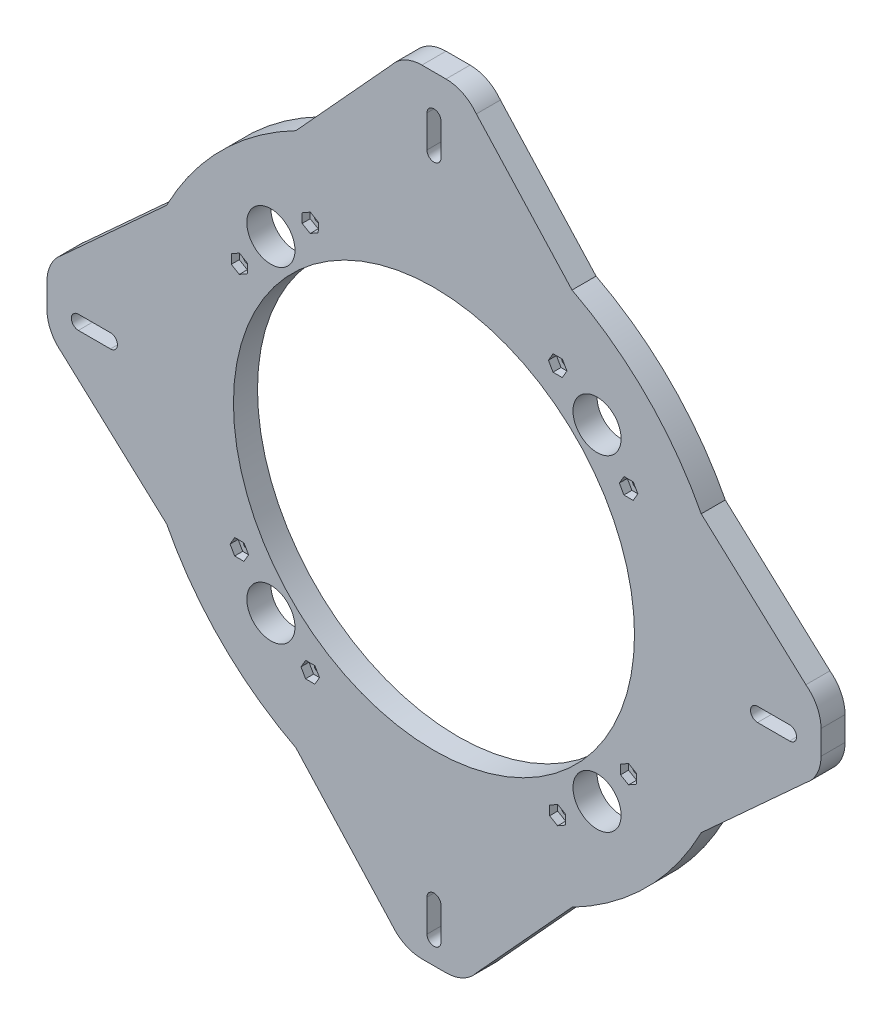
SolidWorks part; units mm, degrees
ref_plane "Plan de face" through (0, 0, 0) normal (0, 0, 1) x (1, 0, 0)
ref_plane "Plan de dessus" through (0, 0, 0) normal (0, 1, 0) x (1, 0, 0)
ref_plane "Plan de droite" through (0, 0, 0) normal (1, 0, 0) x (0, 0, -1)
sketch "Esquisse1" plane through (0, 0, 0) normal (0, 0, 1) x (1, 0, 0)
  circle A1 centre (0, 0) radius 150
  circle A13 centre (0, 0) radius 100
  dimension "D1" = 300
  dimension "D2" = 200
extrude "Boss.-Extru.1" add sketch "Esquisse1" along normal blind 12
sketch "Esquisse2" plane through (0, 0, 12) normal (0, 0, 1) x (1, 0, 0)
  line L0 (0, 100) -> (0, 150) construction
  circle A1 centre (0, 0) radius 150 construction
  circle A2 centre (0, 125) radius 17.5
  circle A3 centre (73.4732, 101.1271) radius 17.5
  circle A4 centre (118.8821, 38.6271) radius 17.5
  circle A5 centre (118.8821, -38.6271) radius 17.5
  circle A6 centre (73.4732, -101.1271) radius 17.5
  circle A7 centre (0, -125) radius 17.5
  circle A8 centre (-73.4732, -101.1271) radius 17.5
  circle A9 centre (-118.8821, -38.6271) radius 17.5
  circle A10 centre (-118.8821, 38.6271) radius 17.5
  circle A11 centre (-73.4732, 101.1271) radius 17.5
  point P29 (0, 0)
  dimension "D1" = 35
  dimension "D2" = 10
extrude "Boss.-Extru.2" add sketch "Esquisse2" along normal blind 12
sketch "Esquisse3" plane through (0, 0, 24) normal (0, 0, 1) x (1, 0, 0)
  circle A0 centre (0, 125) radius 10.5
  circle A1 centre (73.4732, 101.1271) radius 10.5
  circle A2 centre (118.8821, 38.6271) radius 10.5
  circle A3 centre (118.8821, -38.6271) radius 10.5
  circle A4 centre (73.4732, -101.1271) radius 10.5
  circle A5 centre (0, -125) radius 10.5
  circle A6 centre (-73.4732, -101.1271) radius 10.5
  circle A7 centre (-118.8821, -38.6271) radius 10.5
  circle A8 centre (-118.8821, 38.6271) radius 10.5
  circle A9 centre (-73.4732, 101.1271) radius 10.5
  point P23 (0, 0)
  dimension "D1" = 21
  dimension "D2" = 10
extrude "Boss.-Extru.3" add sketch "Esquisse3" along normal blind 9
sketch "Esquisse4" plane through (0, 0, 12) normal (0, 0, 1) x (1, 0, 0)
  line L0 (0, 0) -> (0, 182.4914) construction
  line L1 (-14, 145) -> (-14, 185)
  line L2 (-6, 193) -> (6, 193)
  line L3 (14, 185) -> (14, 145)
  line L4 (-14, 145) -> (14, 145)
  line L5 (0, 154.5361) -> (0, 184.5361) construction
  line L6 (-3.75, 154.5361) -> (-3.75, 184.5361)
  line L7 (3.75, 154.5361) -> (3.75, 184.5361)
  line L8 (145, 14) -> (145, -14)
  line L9 (185, -14) -> (145, -14)
  line L10 (193, 6) -> (193, -6)
  line L11 (145, 14) -> (185, 14)
  line L12 (154.5361, -3.75) -> (184.5361, -3.75)
  line L13 (154.5361, 3.75) -> (184.5361, 3.75)
  line L14 (154.5361, 0) -> (184.5361, 0) construction
  line L15 (14, -145) -> (-14, -145)
  line L16 (-14, -185) -> (-14, -145)
  line L17 (6, -193) -> (-6, -193)
  line L18 (14, -145) -> (14, -185)
  line L19 (-3.75, -154.5361) -> (-3.75, -184.5361)
  line L20 (3.75, -154.5361) -> (3.75, -184.5361)
  line L21 (0, -154.5361) -> (0, -184.5361) construction
  line L22 (-145, -14) -> (-145, 14)
  line L23 (-185, 14) -> (-145, 14)
  line L24 (-193, -6) -> (-193, 6)
  line L25 (-145, -14) -> (-185, -14)
  line L26 (-154.5361, 3.75) -> (-184.5361, 3.75)
  line L27 (-154.5361, -3.75) -> (-184.5361, -3.75)
  line L28 (-154.5361, 0) -> (-184.5361, 0) construction
  arc A0 (14, 185) -> (6, 193) centre (6, 185) ccw
  arc A1 (-6, 193) -> (-14, 185) centre (-6, 185) ccw
  arc A2 (-3.75, 154.5361) -> (3.75, 154.5361) centre (0, 154.5361) ccw
  arc A3 (3.75, 184.5361) -> (-3.75, 184.5361) centre (0, 184.5361) ccw
  arc A4 (185, -14) -> (193, -6) centre (185, -6) ccw
  arc A5 (193, 6) -> (185, 14) centre (185, 6) ccw
  arc A6 (154.5361, 3.75) -> (154.5361, -3.75) centre (154.5361, 0) ccw
  arc A7 (184.5361, -3.75) -> (184.5361, 3.75) centre (184.5361, 0) ccw
  arc A8 (-14, -185) -> (-6, -193) centre (-6, -185) ccw
  arc A9 (6, -193) -> (14, -185) centre (6, -185) ccw
  arc A10 (3.75, -154.5361) -> (-3.75, -154.5361) centre (0, -154.5361) ccw
  arc A11 (-3.75, -184.5361) -> (3.75, -184.5361) centre (0, -184.5361) ccw
  arc A12 (-185, 14) -> (-193, 6) centre (-185, 6) ccw
  arc A13 (-193, -6) -> (-185, -14) centre (-185, -6) ccw
  arc A14 (-154.5361, -3.75) -> (-154.5361, 3.75) centre (-154.5361, 0) ccw
  arc A15 (-184.5361, 3.75) -> (-184.5361, -3.75) centre (-184.5361, 0) ccw
  point P9 (14, 193)
  point P13 (0, 169.5361)
  point P31 (169.5361, 0)
  point P46 (0, -169.5361)
  point P61 (-169.5361, 0)
  point P67 (0, 0)
  dimension "D5" = 8
  dimension "D1" = 145
  dimension "D2" = 48
  dimension "D3" = 14
  dimension "D4" = 14
  dimension "D6" = 7.5
  dimension "D7" = 30
  dimension "D8" = 4
extrude "Boss.-Extru.4" add sketch "Esquisse4" against normal blind 12
sketch "Esquisse5" plane through (0, 0, 12) normal (0, 0, 1) x (1, 0, 0)
  line L0 (-6, 193) -> (6, 193)
  line L1 (0, 0) -> (0, 81.7403) construction
  line L2 (21.1389, 185.4745) -> (78.6763, 122.5066)
  line L3 (-21.1389, 185.4745) -> (-78.6763, 122.5066)
  line L4 (-78.6763, 122.5066) -> (0, 146.4026)
  line L5 (0, 146.4026) -> (78.6763, 122.5066)
  line L6 (146.4026, 0) -> (122.5066, -78.6763)
  line L7 (185.4745, -21.1389) -> (122.5066, -78.6763)
  line L8 (193, 6) -> (193, -6)
  line L9 (185.4745, 21.1389) -> (122.5066, 78.6763)
  line L10 (122.5066, 78.6763) -> (146.4026, 0)
  line L11 (0, -146.4026) -> (-78.6763, -122.5066)
  line L12 (-21.1389, -185.4745) -> (-78.6763, -122.5066)
  line L13 (6, -193) -> (-6, -193)
  line L14 (21.1389, -185.4745) -> (78.6763, -122.5066)
  line L15 (78.6763, -122.5066) -> (0, -146.4026)
  line L16 (-146.4026, 0) -> (-122.5066, 78.6763)
  line L17 (-185.4745, 21.1389) -> (-122.5066, 78.6763)
  line L18 (-193, -6) -> (-193, 6)
  line L19 (-185.4745, -21.1389) -> (-122.5066, -78.6763)
  line L20 (-122.5066, -78.6763) -> (-146.4026, 0)
  arc A0 (6, 193) -> (21.1389, 185.4745) centre (6, 174.0098) cw
  arc A1 (-6, 193) -> (-21.1389, 185.4745) centre (-6, 174.0098) ccw
  arc A2 (193, -6) -> (185.4745, -21.1389) centre (174.0098, -6) cw
  arc A3 (193, 6) -> (185.4745, 21.1389) centre (174.0098, 6) ccw
  arc A4 (-6, -193) -> (-21.1389, -185.4745) centre (-6, -174.0098) cw
  arc A5 (6, -193) -> (21.1389, -185.4745) centre (6, -174.0098) ccw
  arc A6 (-193, 6) -> (-185.4745, 21.1389) centre (-174.0098, 6) cw
  arc A7 (-193, -6) -> (-185.4745, -21.1389) centre (-174.0098, -6) ccw
  point P45 (0, 0)
  dimension "D1" = 4
extrude "Boss.-Extru.5" add sketch "Esquisse5" against normal blind 12
sketch "Esquisse6" plane through (0, 0, 12) normal (0, 0, 1) x (1, 0, 0)
  line L0 (0, 0) -> (0, 165.5959) construction
  line L1 (0, 157.5959) -> (0, 173.5959) construction
  line L2 (-3.5, 157.5959) -> (-3.5, 173.5959)
  line L3 (3.5, 157.5959) -> (3.5, 173.5959)
  line L4 (161.3293, -7.2333) -> (177.3293, -7.2333)
  line L5 (161.3293, -0.2333) -> (177.3293, -0.2333)
  line L6 (161.3293, -3.7333) -> (177.3293, -3.7333) construction
  line L7 (-3.5, -165.0626) -> (-3.5, -181.0626)
  line L8 (3.5, -165.0626) -> (3.5, -181.0626)
  line L9 (0, -165.0626) -> (0, -181.0626) construction
  line L10 (-161.3293, -0.2333) -> (-177.3293, -0.2333)
  line L11 (-161.3293, -7.2333) -> (-177.3293, -7.2333)
  line L12 (-161.3293, -3.7333) -> (-177.3293, -3.7333) construction
  arc A0 (-3.5, 157.5959) -> (3.5, 157.5959) centre (0, 157.5959) ccw
  arc A1 (3.5, 173.5959) -> (-3.5, 173.5959) centre (0, 173.5959) ccw
  arc A2 (161.3293, -0.2333) -> (161.3293, -7.2333) centre (161.3293, -3.7333) ccw
  arc A3 (177.3293, -7.2333) -> (177.3293, -0.2333) centre (177.3293, -3.7333) ccw
  arc A4 (3.5, -165.0626) -> (-3.5, -165.0626) centre (0, -165.0626) ccw
  arc A5 (-3.5, -181.0626) -> (3.5, -181.0626) centre (0, -181.0626) ccw
  arc A6 (-161.3293, -7.2333) -> (-161.3293, -0.2333) centre (-161.3293, -3.7333) ccw
  arc A7 (-177.3293, -0.2333) -> (-177.3293, -7.2333) centre (-177.3293, -3.7333) ccw
  point P5 (0, 165.5959)
  point P12 (0, 0)
  point P15 (169.3293, -3.7333)
  point P22 (0, -173.0626)
  point P29 (-169.3293, -3.7333)
  point P34 (0, -3.7333)
  point P35 (0, 165.5959)
  point P36 (0, 0)
  dimension "D2" = 165.5959
  dimension "D4" = 8
  dimension "D1" = 7
  dimension "D3" = 4
extrude "Enlèv. mat.-Extru.1" cut sketch "Esquisse6" against normal through all
sketch "Esquisse7" plane through (0, 0, 0) normal (0, 1, 0) x (1, 0, 0)
  line L0 (-133.27, -12) -> (-185.4745, -12) construction
  line L1 (-156.0109, -12) -> (175.7655, -12)
  line L2 (-156.0109, -12) -> (-156.0109, -65.1268)
  line L3 (-156.0109, -65.1268) -> (175.7655, -65.1268)
  line L4 (175.7655, -12) -> (175.7655, -65.1268)
extrude "Enlèv. mat.-Extru.2" cut sketch "Esquisse7" against normal mid plane 572
sketch "Esquisse8" plane through (0, 0, 12) normal (0, 0, 1) x (1, 0, 0)
  line L0 (0, 0) -> (0, 94.3932) construction
  line L1 (0, 0) -> (-135.3624, 135.3624) construction
  line L2 (-106.066, 106.066) -> (-56.5685, 56.5685) construction
  arc A0 (-68.8412, 133.27) -> (-133.27, 68.8412) centre (0, 0) ccw construction
  circle A1 centre (81.3173, 81.3173) radius 12
  circle A2 centre (-81.3173, 81.3173) radius 12
  circle A7 centre (81.3173, -81.3173) radius 12
  circle A8 centre (-81.3173, -81.3173) radius 12
  circle A9 centre (0, 0) radius 100 construction
  point P21 (0, 0)
  point P24 (0, 0)
  dimension "D1" = 24
  dimension "D3" = 115
  dimension "D2" = 4
extrude "Enlèv. mat.-Extru.3" cut sketch "Esquisse8" against normal mid plane 572
sketch "Esquisse10" plane through (0, 0, 0) normal (0, 0, 1) x (1, 0, 0)
  line L0 (-227.0764, 0) -> (263.6693, 0) construction
  line L1 (263.6693, 0) -> (0, 0) construction
  line L2 (0, 0) -> (142.7373, 142.7373) construction
  line L3 (142.7373, 142.7373) -> (-131.2081, -131.2081) construction
  line L4 (-131.2081, -131.2081) -> (0, 0) construction
  line L5 (0, 0) -> (-135.9701, 135.9701) construction
  line L6 (-135.9701, 135.9701) -> (134.4663, -134.4663) construction
  line L7 (-65.7077, 94.7632) -> (-61.7207, 92.4315)
  line L8 (-101.6689, -61.669) -> (-99.382, -65.6819)
  line L9 (-99.382, -65.6819) -> (-94.7632, -65.7077)
  line L10 (-94.7632, -65.7077) -> (-92.4315, -61.7207)
  line L11 (-92.4315, -61.7207) -> (-94.7184, -57.7079)
  line L12 (-94.7184, -57.7079) -> (-99.3372, -57.682)
  line L13 (-99.3372, -57.682) -> (-101.6689, -61.669)
  line L14 (-57.0761, -97.0761) -> (-59.3631, -93.0632)
  line L15 (-59.3631, -93.0632) -> (-63.9818, -93.0373)
  line L16 (-63.9818, -93.0373) -> (-66.3136, -97.0244)
  line L17 (-66.3136, -97.0244) -> (-64.0266, -101.0372)
  line L18 (-64.0266, -101.0372) -> (-59.4079, -101.0631)
  line L19 (-59.4079, -101.0631) -> (-57.0761, -97.0761)
  line L20 (-65.6819, 99.382) -> (-65.7077, 94.7632)
  line L21 (-61.669, 101.6689) -> (-65.6819, 99.382)
  line L22 (-57.682, 99.3372) -> (-61.669, 101.6689)
  line L23 (-57.7079, 94.7184) -> (-57.682, 99.3372)
  line L24 (-61.7207, 92.4315) -> (-57.7079, 94.7184)
  line L25 (-101.0372, 64.0266) -> (-101.0631, 59.4079)
  line L26 (-101.0631, 59.4079) -> (-97.0761, 57.0761)
  line L27 (-97.0761, 57.0761) -> (-93.0632, 59.3631)
  line L28 (-93.0632, 59.3631) -> (-93.0373, 63.9818)
  line L29 (-93.0373, 63.9818) -> (-97.0244, 66.3136)
  line L30 (-97.0244, 66.3136) -> (-101.0372, 64.0266)
  line L31 (94.7632, 65.7077) -> (92.4315, 61.7207)
  line L32 (99.382, 65.6819) -> (94.7632, 65.7077)
  line L33 (101.6689, 61.669) -> (99.382, 65.6819)
  line L34 (99.3372, 57.682) -> (101.6689, 61.669)
  line L35 (94.7184, 57.7079) -> (99.3372, 57.682)
  line L36 (92.4315, 61.7207) -> (94.7184, 57.7079)
  line L37 (64.0266, 101.0372) -> (59.4079, 101.0631)
  line L38 (59.4079, 101.0631) -> (57.0761, 97.0761)
  line L39 (57.0761, 97.0761) -> (59.3631, 93.0632)
  line L40 (59.3631, 93.0632) -> (63.9818, 93.0373)
  line L41 (63.9818, 93.0373) -> (66.3136, 97.0244)
  line L42 (66.3136, 97.0244) -> (64.0266, 101.0372)
  line L43 (65.7077, -94.7632) -> (61.7207, -92.4315)
  line L44 (65.6819, -99.382) -> (65.7077, -94.7632)
  line L45 (61.669, -101.6689) -> (65.6819, -99.382)
  line L46 (57.682, -99.3372) -> (61.669, -101.6689)
  line L47 (57.7079, -94.7184) -> (57.682, -99.3372)
  line L48 (61.7207, -92.4315) -> (57.7079, -94.7184)
  line L49 (101.0372, -64.0266) -> (101.0631, -59.4079)
  line L50 (101.0631, -59.4079) -> (97.0761, -57.0761)
  line L51 (97.0761, -57.0761) -> (93.0632, -59.3631)
  line L52 (93.0632, -59.3631) -> (93.0373, -63.9818)
  line L53 (93.0373, -63.9818) -> (97.0244, -66.3136)
  line L54 (97.0244, -66.3136) -> (101.0372, -64.0266)
  circle A0 centre (0, 0) radius 115 construction
  circle A1 centre (-97.0502, -61.6949) radius 4 construction
  circle A2 centre (-61.6949, -97.0502) radius 4 construction
  point P65 (0, 0)
  dimension "D1" = 230
  dimension "D2" = 8
  dimension "D3" = 8
  dimension "D4" = 25
  dimension "D5" = 25
  dimension "D7" = 45
  dimension "D6" = 4
extrude "Enlèv. mat.-Extru.5" cut sketch "Esquisse10" against normal blind 4 from offset 12
sketch "Esquisse11" plane through (0, 0, 0) normal (0, 0, 1) x (1, 0, 0)
  line L0 (0, 0) -> (126.5991, 126.5991) construction
  line L1 (126.5991, 126.5991) -> (0, 0) construction
  line L2 (0, 0) -> (-134.2603, 134.2603) construction
  line L3 (-134.2603, 134.2603) -> (136.4381, -136.4381) construction
  line L4 (136.4381, -136.4381) -> (0, 0) construction
  line L5 (0, 0) -> (-128.6837, -128.6837) construction
  line L6 (0, 0) -> (-281.9897, 0) construction
  circle A0 centre (0, 0) radius 115 construction
  circle A1 centre (-97.0502, -61.6949) radius 2
  circle A2 centre (-61.6949, -97.0502) radius 2
  circle A3 centre (-61.6949, 97.0502) radius 2
  circle A4 centre (-97.0502, 61.6949) radius 2
  circle A5 centre (97.0502, 61.6949) radius 2
  circle A6 centre (61.6949, 97.0502) radius 2
  circle A7 centre (61.6949, -97.0502) radius 2
  circle A8 centre (97.0502, -61.6949) radius 2
  point P27 (0, 0)
  dimension "D1" = 230
  dimension "D2" = 25
  dimension "D3" = 25
  dimension "D4" = 4
  dimension "D5" = 4
  dimension "D6" = 45
  dimension "D7" = 4
extrude "Enlèv. mat.-Extru.6" cut sketch "Esquisse11" along normal blind 10
